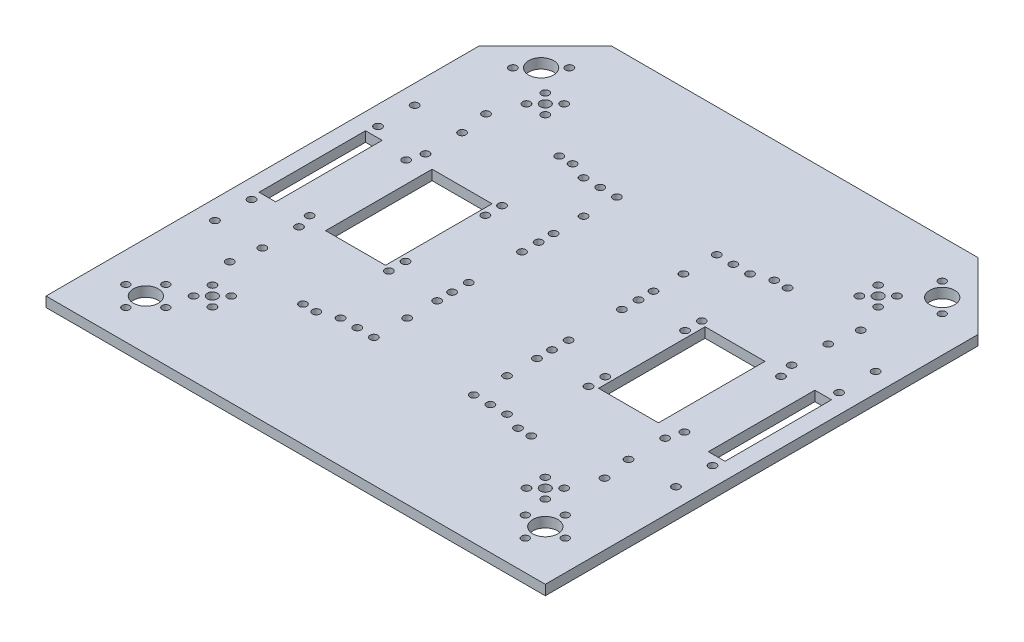
SolidWorks part; units mm, degrees
ref_plane "Plan de face" through (0, 0, 0) normal (0, 0, 1) x (1, 0, 0)
ref_plane "Plan de dessus" through (0, 0, 0) normal (0, 1, 0) x (1, 0, 0)
ref_plane "Plan de droite" through (0, 0, 0) normal (1, 0, 0) x (0, 0, -1)
sketch "Esquisse1" plane through (0, 0, 0) normal (0, 1, 0) x (1, 0, 0)
  line L0 (-150, 0) -> (-150, 260)
  line L2 (150, 0) -> (150, 260)
  line L3 (-150, 260) -> (-110, 260) construction
  line L4 (-110, 260) -> (-110, 300) construction
  line L5 (150, 260) -> (110, 260) construction
  line L6 (110, 260) -> (110, 300) construction
  line L8 (-150, 260) -> (-110, 300)
  line L9 (-110, 300) -> (110, 300)
  line L10 (0, 0) -> (0, 300) construction
  line L11 (110, 300) -> (150, 260)
  line L12 (-150, 0) -> (-120, 0) construction
  line L13 (-120, 18) -> (-120, 0) construction
  line L14 (150, 0) -> (120, 0) construction
  line L15 (120, 18) -> (120, 0) construction
  line L17 (-150, 260) -> (-120, 260) construction
  line L18 (-120, 260) -> (-120, 267.5) construction
  line L19 (150, 260) -> (120, 260) construction
  line L20 (120, 260) -> (120, 268.5) construction
  line L21 (-120, 267.5) -> (-111.5147, 275.9853) construction
  line L22 (-120, 267.5) -> (-128.4853, 259.0147) construction
  line L23 (120, 268.5) -> (128.4853, 260.0147) construction
  line L24 (120, 268.5) -> (111.5147, 276.9853) construction
  line L25 (-150, 0) -> (150, 0) construction
  line L26 (120, 30) -> (120, 18) construction
  line L27 (120, 30) -> (120, 42) construction
  line L28 (-150, 0) -> (150, 0)
  line L29 (-120, 18) -> (-120, 30) construction
  line L30 (-120, 30) -> (-120, 42) construction
  line L32 (150, 150) -> (-150, 150) construction
  line L33 (-120, 30) -> (-108, 30) construction
  line L34 (-120, 30) -> (-132, 30) construction
  line L35 (120, 30) -> (132, 30) construction
  line L36 (120, 30) -> (108, 30) construction
  circle A2 centre (-120, 30) radius 7.5
  circle A4 centre (-120, 267.5) radius 7.5
  circle A5 centre (120, 268.5) radius 7.5
  circle A6 centre (-111.5147, 275.9853) radius 2.3
  circle A7 centre (-128.4853, 259.0147) radius 2.3
  circle A8 centre (111.5147, 276.9853) radius 2.2
  circle A9 centre (128.4853, 260.0147) radius 2.2
  circle A10 centre (120, 30) radius 7.5
  circle A11 centre (120, 42) radius 2.2
  circle A13 centre (-120, 42) radius 2.2
  circle A14 centre (-120, 18) radius 2.2
  circle A16 centre (-132, 30) radius 2.2
  circle A17 centre (-108, 30) radius 2.2
  circle A18 centre (108, 30) radius 2.2
  circle A19 centre (132, 30) radius 2.2
  circle A20 centre (120, 18) radius 2.2
extrude "Boss.-Extru.1" add sketch "Esquisse1" along normal blind 6
sketch "Esquisse7" plane through (0, 6, 0) normal (0, 1, 0) x (1, 0, 0)
  line L0 (0, 150) -> (-130, 150) construction
  line L1 (0, 0) -> (0, 300) construction
  line L2 (150, 150) -> (-150, 150) construction
  line L3 (-130, 150) -> (-130, 182)
  line L4 (-130, 182) -> (-140, 182)
  line L5 (-140, 182) -> (-140, 118)
  line L6 (-140, 118) -> (-130, 118)
  line L7 (-130, 118) -> (-130, 150)
extrude "Enlèv. mat.-Extru.9" cut sketch "Esquisse7" against normal blind 10.5
sketch "Esquisse6" plane through (0, 6, 0) normal (0, 1, 0) x (1, 0, 0)
  line L0 (-142.5, 116) -> (-134.5, 116) construction
  line L2 (-142.5, 116) -> (-142.5, 150) construction
  line L3 (-142.5, 116) -> (-142.5, 108) construction
  line L11 (-142.5, 108) -> (-134.5, 108) construction
  line L12 (-134.5, 108) -> (-134.5, 116) construction
  line L14 (-142.5, 150) -> (-150, 150) construction
  line L15 (-142.5, 116) -> (-106, 116) construction
  line L16 (-106, 116) -> (-106, 108) construction
  line L17 (-106, 108) -> (-114, 108) construction
  line L18 (-114, 108) -> (-114, 116) construction
  line L19 (-114, 116) -> (-134.5, 116) construction
  line L20 (-134.5, 116) -> (-134.5, 86) construction
  line L21 (-134.5, 86) -> (-142.5, 86) construction
  line L22 (-142.5, 86) -> (-142.5, 94) construction
  line L23 (-142.5, 94) -> (-134.5, 94) construction
  line L24 (-134.5, 94) -> (-134.5, 86) construction
  line L25 (-134.5, 86) -> (-114, 86) construction
  line L26 (-114, 86) -> (-114, 94) construction
  line L27 (-114, 94) -> (-106, 94) construction
  line L28 (-106, 94) -> (-106, 86) construction
  line L29 (-106, 86) -> (-114, 86) construction
  line L30 (-106, 94) -> (-114, 86) construction
  line L31 (-114, 94) -> (-106, 86) construction
  line L32 (-142.5, 94) -> (-134.5, 86) construction
  line L33 (-142.5, 86) -> (-134.5, 94) construction
  line L34 (-142.5, 116) -> (-134.5, 108) construction
  line L35 (-142.5, 108) -> (-134.5, 116) construction
  line L38 (150, 150) -> (142.5, 150) construction
  line L39 (150, 150) -> (-150, 150) construction
  line L40 (142.5, 150) -> (142.5, 184) construction
  line L41 (142.5, 184) -> (142.5, 192) construction
  line L42 (142.5, 184) -> (134.5, 184) construction
  line L43 (134.5, 184) -> (134.5, 192) construction
  line L44 (134.5, 192) -> (142.5, 192) construction
  line L45 (142.5, 184) -> (106, 184) construction
  line L46 (106, 184) -> (106, 192) construction
  line L47 (106, 192) -> (114, 192) construction
  line L48 (114, 192) -> (114, 184) construction
  line L49 (114, 184) -> (134.5, 184) construction
  line L50 (114, 184) -> (114, 214) construction
  line L51 (114, 214) -> (134.5, 214) construction
  line L52 (134.5, 214) -> (134.5, 184) construction
  line L53 (114, 214) -> (106, 214) construction
  line L54 (106, 214) -> (106, 206) construction
  line L55 (106, 206) -> (114, 206) construction
  line L56 (114, 206) -> (106, 214) construction
  line L57 (106, 206) -> (114, 214) construction
  line L58 (134.5, 214) -> (142.5, 214) construction
  line L59 (142.5, 214) -> (142.5, 206) construction
  line L60 (142.5, 206) -> (134.5, 206) construction
  line L61 (134.5, 206) -> (142.5, 214) construction
  line L62 (134.5, 214) -> (142.5, 206) construction
  line L63 (134.5, 192) -> (142.5, 184) construction
  line L64 (142.5, 192) -> (134.5, 184) construction
  line L65 (106, 192) -> (114, 184) construction
  line L66 (106, 184) -> (114, 192) construction
  line L71 (-114, 116) -> (-106, 108) construction
  line L72 (-114, 108) -> (-106, 116) construction
  line L73 (-114, 116) -> (-114, 86) construction
  circle A16 centre (110, 210) radius 2.3
  circle A17 centre (138.5, 210) radius 2.3
  circle A18 centre (138.5, 188) radius 2.3
  circle A19 centre (110, 188) radius 2.3
  circle A20 centre (-138.5, 90) radius 2.3
  circle A21 centre (-138.5, 112) radius 2.3
  circle A22 centre (-110, 112) radius 2.3
  circle A23 centre (-110, 90) radius 2.3
  dimension "D3" = 34
  dimension "D4" = 7.5
  dimension "D1" = 7.5
  dimension "D2" = 34
sketch "Esquisse4" plane through (0, 6, 0) normal (0, 1, 0) x (1, 0, 0)
  line L0 (-150, 150) -> (-100, 150) construction
  line L8 (150, 150) -> (-150, 150) construction
  line L14 (-100, 150) -> (-100, 182)
  line L15 (-100, 250) -> (-100, 50) construction
  line L16 (-100, 150) -> (-100, 118)
  line L17 (-100, 118) -> (-64, 118)
  line L18 (-64, 118) -> (-64, 182)
  line L19 (-64, 182) -> (-100, 182)
sketch "Esquisse9" plane through (0, 6, 0) normal (0, 1, 0) x (1, 0, 0)
  line L0 (-150, 0) -> (150, 0) construction
  line L1 (150, 0) -> (150, 300) construction
  line L2 (150, 300) -> (-150, 300) construction
  line L3 (-150, 300) -> (-150, 0) construction
  line L4 (-100, 50) -> (-94.3431, 55.6569) construction
  line L5 (-150, 0) -> (-150, 300) construction
  line L6 (150, 0) -> (0, 0) construction
  line L7 (0, 0) -> (0, 50) construction
  line L8 (0, 0) -> (0, 300) construction
  line L9 (0, 50) -> (100, 50) construction
  line L10 (100, 50) -> (100, 250) construction
  line L11 (100, 250) -> (-100, 250) construction
  line L12 (-100, 250) -> (-100, 50) construction
  line L13 (-100, 50) -> (0, 50) construction
  line L14 (-100, 250) -> (-94.3431, 244.3431) construction
  line L15 (-100, 250) -> (-105.6569, 255.6569) construction
  line L16 (100, 50) -> (94.3431, 55.6569) construction
  line L17 (100, 250) -> (105.6569, 255.6569) construction
  line L18 (100, 250) -> (94.3431, 244.3431) construction
  line L19 (100, 50) -> (105.6569, 44.3431) construction
  line L20 (-100, 50) -> (-105.6569, 44.3431) construction
  line L21 (-150, 0) -> (150, 300) construction
  line L22 (-100, 50) -> (-94.3431, 44.3431) construction
  line L23 (-100, 50) -> (-105.6569, 55.6569) construction
  line L24 (100, 50) -> (105.6569, 55.6569) construction
  line L25 (100, 50) -> (94.3431, 44.3431) construction
  line L26 (100, 250) -> (105.6569, 244.3431) construction
  line L27 (100, 250) -> (94.3431, 255.6569) construction
  line L28 (-100, 250) -> (-94.3431, 255.6569) construction
  line L29 (-100, 250) -> (-105.6569, 244.3431) construction
  circle A0 centre (-100, 50) radius 3
  circle A1 centre (100, 50) radius 3
  circle A2 centre (100, 250) radius 3
  circle A3 centre (-100, 250) radius 3
  circle A4 centre (-105.6569, 255.6569) radius 2.3
  circle A5 centre (-94.3431, 244.3431) radius 2.3
  circle A6 centre (94.3431, 244.3431) radius 2.3
  circle A7 centre (105.6569, 255.6569) radius 2.3
  circle A8 centre (94.3431, 55.6569) radius 2.3
  circle A9 centre (105.6569, 44.3431) radius 2.3
  circle A10 centre (-105.6569, 44.3431) radius 2.3
  circle A11 centre (-94.3431, 55.6569) radius 2.3
  circle A12 centre (-105.6569, 55.6569) radius 2.3
  circle A13 centre (-94.3431, 44.3431) radius 2.3
  circle A14 centre (105.6569, 55.6569) radius 2.3
  circle A15 centre (94.3431, 44.3431) radius 2.3
  circle A16 centre (105.6569, 244.3431) radius 2.3
  circle A17 centre (94.3431, 255.6569) radius 2.3
  circle A18 centre (-94.3431, 255.6569) radius 2.3
  circle A19 centre (-105.6569, 244.3431) radius 2.3
extrude "Enlèv. mat.-Extru.10" cut sketch "Esquisse6" against normal blind 50
extrude "Enlèv. mat.-Extru.11" cut sketch "Esquisse4" against normal blind 50
sketch "Esquisse3" plane through (0, 6, 0) normal (0, 1, 0) x (1, 0, 0)
  line L6 (-150, 150) -> (-64, 150) construction
  line L7 (-64, 118) -> (-64, 182) construction
  line L8 (-64, 150) -> (-64, 178) construction
  line L9 (-64, 178) -> (-56, 178) construction
  line L10 (-56, 178) -> (-56, 170) construction
  line L11 (-56, 170) -> (-59, 170) construction
  line L16 (-64, 150) -> (-64, 112) construction
  line L17 (-64, 112) -> (-56, 112) construction
  line L25 (-56, 112) -> (-56, 120) construction
  line L26 (-64, 120) -> (-34, 120) construction
  line L27 (-56, 170) -> (-64, 178) construction
  line L28 (-64, 178) -> (-56, 178) construction
  line L29 (-56, 178) -> (-64, 170) construction
  line L30 (-34, 120) -> (-26, 120) construction
  line L31 (-56, 112) -> (-64, 120) construction
  line L32 (-64, 120) -> (-56, 120) construction
  line L33 (-56, 120) -> (-64, 112) construction
  line L37 (-26, 120) -> (-26, 128) construction
  line L38 (-26, 128) -> (-34, 128) construction
  line L39 (-34, 128) -> (-26, 120) construction
  line L43 (-26, 120) -> (-34, 120) construction
  line L55 (150, 150) -> (64, 150) construction
  line L56 (150, 150) -> (-150, 150) construction
  line L57 (64, 150) -> (64, 170) construction
  line L58 (34, 130) -> (26, 130) construction
  line L61 (64, 150) -> (64, 130) construction
  line L62 (64, 130) -> (59, 130) construction
  line L63 (59, 130) -> (59, 165) construction
  line L66 (59, 165) -> (39, 165) construction
  line L70 (39, 165) -> (39, 130) construction
  line L72 (39, 130) -> (34, 130) construction
  line L73 (34, 130) -> (34, 180) construction
  line L74 (34, 180) -> (64, 180) construction
  line L76 (64, 180) -> (64, 130) construction
  line L77 (-34, 120) -> (-26, 128) construction
  line L78 (26, 130) -> (26, 138) construction
  line L79 (-34, 120) -> (-34, 170) construction
  line L80 (-39, 170) -> (-34, 170) construction
  line L81 (-34, 170) -> (-26, 170) construction
  line L82 (-26, 170) -> (-26, 162) construction
  line L83 (-26, 162) -> (-34, 162) construction
  line L84 (-34, 162) -> (-26, 170) construction
  line L85 (-26, 170) -> (-34, 170) construction
  line L86 (-34, 170) -> (-26, 162) construction
  line L87 (26, 138) -> (34, 138) construction
  line L88 (-59, 170) -> (-59, 138) construction
  line L89 (-59, 138) -> (-39, 138) construction
  line L90 (-39, 138) -> (-39, 170) construction
  line L91 (34, 138) -> (26, 130) construction
  line L92 (26, 130) -> (26, 138) construction
  line L93 (26, 138) -> (34, 130) construction
  line L94 (34, 130) -> (34, 180) construction
  line L95 (34, 180) -> (26, 180) construction
  line L96 (26, 180) -> (26, 172) construction
  line L97 (26, 172) -> (34, 172) construction
  line L98 (34, 172) -> (26, 180) construction
  line L99 (26, 180) -> (26, 172) construction
  line L100 (26, 172) -> (34, 180) construction
  line L101 (64, 180) -> (64, 188) construction
  line L102 (64, 188) -> (56, 188) construction
  line L103 (56, 188) -> (56, 180) construction
  line L104 (56, 180) -> (64, 188) construction
  line L105 (64, 188) -> (56, 188) construction
  line L106 (56, 188) -> (64, 180) construction
  line L107 (64, 180) -> (64, 130) construction
  line L108 (64, 130) -> (64, 122) construction
  line L109 (64, 122) -> (56, 122) construction
  line L110 (56, 122) -> (56, 130) construction
  line L111 (56, 130) -> (59, 130) construction
  line L112 (64, 122) -> (56, 130) construction
  line L113 (56, 130) -> (56, 122) construction
  line L114 (56, 122) -> (64, 130) construction
  circle A8 centre (-60, 174) radius 2.3
  circle A10 centre (-60, 116) radius 2.3
  circle A12 centre (-30, 166) radius 2.3
  circle A13 centre (-30, 124) radius 2.3
  circle A14 centre (60, 184) radius 2.3
  circle A15 centre (30, 176) radius 2.3
  circle A16 centre (30, 134) radius 2.3
  circle A17 centre (60, 126) radius 2.3
mirror "Symétrie1" about plane through (0, 0, 0) normal (1, 0, 0) of "Enlèv. mat.-Extru.9"
mirror "Symétrie2" about plane through (0, 0, 0) normal (1, 0, 0) of "Enlèv. mat.-Extru.11"
mirror "Symétrie3" about plane through (0, 0, 0) normal (1, 0, 0) of "Enlèv. mat.-Extru.10"
extrude "Enlèv. mat.-Extru.12" cut sketch "Esquisse9" against normal blind 35
extrude "Enlèv. mat.-Extru.13" cut sketch "Esquisse3" against normal blind 35
mirror "Symétrie4" about plane through (0, 0, 0) normal (1, 0, 0) of "Enlèv. mat.-Extru.13"
sketch "Esquisse10" plane through (0, 6, 0) normal (0, 1, 0) x (1, 0, 0)
  line L0 (0, 150) -> (0, 205) construction
  line L1 (0, 205) -> (-41.6, 205) construction
  line L2 (0, 205) -> (-56.6, 205) construction
  line L3 (-41.6, 205) -> (-56.6, 205) construction
  line L4 (-56.6, 205) -> (-56.6, 223) construction
  line L5 (-56.6, 223) -> (-116.6, 223) construction
  line L6 (-116.6, 223) -> (-116.6, 187) construction
  line L7 (-116.6, 187) -> (-56.6, 187) construction
  line L8 (-56.6, 187) -> (-56.6, 205) construction
  line L9 (-116.6, 223) -> (-116.6, 231) construction
  line L10 (-116.6, 231) -> (-108.6, 231) construction
  line L11 (-108.6, 223) -> (-116.6, 231) construction
  line L12 (-116.6, 231) -> (-108.6, 231) construction
  line L13 (-108.6, 231) -> (-116.6, 223) construction
  line L14 (-116.6, 223) -> (-116.6, 187) construction
  line L15 (-116.6, 187) -> (-116.6, 175) construction
  line L16 (-116.6, 175) -> (-108.6, 175) construction
  line L17 (41.6, 95) -> (56.6, 95) construction
  line L18 (-108.6, 175) -> (-108.6, 187) construction
  line L19 (-116.6, 175) -> (-116.6, 183) construction
  line L20 (-116.6, 183) -> (-108.6, 183) construction
  line L21 (-108.6, 183) -> (-116.6, 175) construction
  line L22 (-116.6, 175) -> (-116.6, 183) construction
  line L23 (-116.6, 183) -> (-108.6, 175) construction
  line L24 (116.6, 113) -> (116.6, 125) construction
  line L25 (116.6, 125) -> (108.6, 125) construction
  line L26 (-56.6, 223) -> (-56.6, 231) construction
  line L27 (-56.6, 231) -> (-72.6, 231) construction
  line L28 (-72.6, 231) -> (-72.6, 223) construction
  line L29 (-72.6, 223) -> (-64.6, 223) construction
  line L30 (-64.6, 223) -> (-64.6, 231) construction
  line L31 (-64.6, 231) -> (-56.6, 223) construction
  line L32 (-56.6, 223) -> (-56.6, 231) construction
  line L33 (-56.6, 231) -> (-64.6, 223) construction
  line L34 (-64.6, 223) -> (-72.6, 231) construction
  line L35 (-72.6, 231) -> (-65.407, 231) construction
  line L36 (0, 205) -> (37.8301, 205) construction
  line L37 (56.6, 77) -> (116.6, 77) construction
  line L38 (-41.6, 205) -> (-56.6, 205) construction
  line L39 (116.6, 77) -> (116.6, 113) construction
  line L40 (116.6, 113) -> (56.6, 113) construction
  line L41 (56.6, 113) -> (56.6, 77) construction
  line L42 (0, 95) -> (41.6, 95) construction
  line L43 (56.6, 95) -> (56.6, 77) construction
  line L44 (56.6, 77) -> (56.6, 69) construction
  line L45 (56.6, 69) -> (72.6, 69) construction
  line L46 (72.6, 69) -> (72.6, 77) construction
  line L47 (56.6, 113) -> (56.6, 95) construction
  line L48 (56.6, 95) -> (56.6, 77) construction
  line L49 (72.6, 77) -> (64.6, 77) construction
  line L50 (64.6, 77) -> (64.6, 69) construction
  line L51 (64.6, 69) -> (72.6, 77) construction
  line L52 (72.6, 77) -> (72.6, 69) construction
  line L53 (72.6, 69) -> (64.6, 77) construction
  line L54 (64.6, 77) -> (56.6, 69) construction
  line L55 (56.6, 69) -> (56.6, 77) construction
  line L56 (56.6, 77) -> (64.6, 69) construction
  line L57 (64.6, 69) -> (64.6, 77) construction
  line L58 (64.6, 77) -> (116.6, 77) construction
  line L59 (116.6, 77) -> (116.6, 69) construction
  line L60 (116.6, 69) -> (108.6, 69) construction
  line L61 (108.6, 69) -> (108.6, 77) construction
  line L62 (108.6, 77) -> (116.6, 69) construction
  line L63 (116.6, 69) -> (116.6, 77) construction
  line L64 (116.6, 77) -> (108.6, 69) construction
  line L65 (108.6, 69) -> (116.6, 69) construction
  line L66 (116.6, 69) -> (116.6, 113) construction
  line L67 (108.6, 125) -> (108.6, 113) construction
  line L68 (116.6, 113) -> (116.6, 125) construction
  line L69 (116.6, 125) -> (116.6, 117) construction
  line L70 (116.6, 117) -> (108.6, 117) construction
  line L71 (108.6, 117) -> (116.6, 125) construction
  line L72 (108.6, 125) -> (116.6, 117) construction
  line L78 (0, 0) -> (0, 300) construction
  line L79 (0, 150) -> (0, 95) construction
  circle A9 centre (-112.6, 227) radius 2.3
  circle A10 centre (-68.6, 227) radius 2.3
  circle A11 centre (-60.6, 227) radius 2.3
  circle A13 centre (112.6, 73) radius 2.3
  circle A14 centre (68.6, 73) radius 2.3
  circle A15 centre (60.6, 73) radius 2.3
  circle A16 centre (-112.6, 179) radius 2.3
  circle A17 centre (112.6, 121) radius 2.3
extrude "Enlèv. mat.-Extru.14" cut sketch "Esquisse10" against normal blind 10
mirror "Symétrie5" about plane through (0, 0, 0) normal (1, 0, 0) of "Enlèv. mat.-Extru.14"
sketch "Esquisse11" plane through (0, 6, 0) normal (0, 1, 0) x (1, 0, 0)
  line L0 (0, 150) -> (0, 185) construction
  line L1 (0, 0) -> (0, 300) construction
  line L2 (0, 185) -> (-30, 185) construction
  line L3 (-30, 185) -> (-30, 235) construction
  line L4 (-30, 185) -> (-30, 193) construction
  line L5 (0, 150) -> (0, 115) construction
  line L6 (0, 115) -> (30, 115) construction
  line L7 (30, 107) -> (30, 72) construction
  line L8 (30, 115) -> (30, 107) construction
  line L9 (-30, 223) -> (-38, 223) construction
  line L12 (-30, 213) -> (-38, 213) construction
  circle A7 centre (30, 97) radius 2.3
  circle A9 centre (30, 77) radius 2.3
  circle A11 centre (-30, 203) radius 2.3
  circle A13 centre (-30, 223) radius 2.3
  circle A17 centre (-30, 185) radius 2.3
  circle A18 centre (30, 115) radius 2.3
  circle A19 centre (-40, 223) radius 2.3
  circle A20 centre (-50, 223) radius 2.3
  circle A21 centre (40, 77) radius 2.3
  circle A22 centre (50, 77) radius 2.3
extrude "Enlèv. mat.-Extru.15" cut sketch "Esquisse11" against normal blind 10
mirror "Symétrie6" about plane through (0, 0, 0) normal (1, 0, 0) of "Enlèv. mat.-Extru.15"
